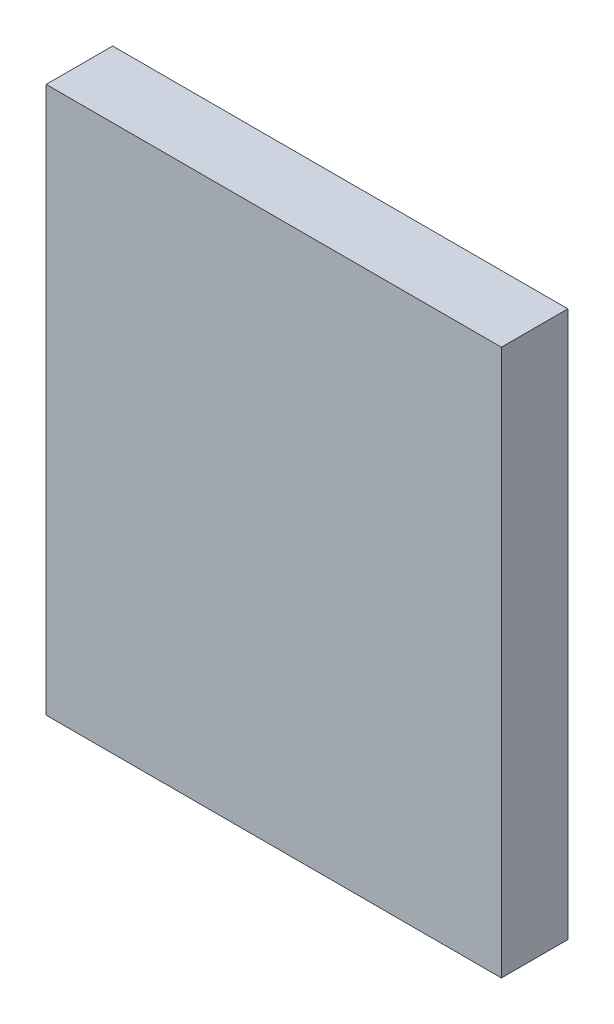
SolidWorks part; units mm, degrees
ref_plane "Front Plane" through (0, 0, 0) normal (0, 0, 1) x (1, 0, 0)
ref_plane "Top Plane" through (0, 0, 0) normal (0, 1, 0) x (1, 0, 0)
ref_plane "Right Plane" through (0, 0, 0) normal (1, 0, 0) x (0, 0, -1)
sketch "Sketch3" plane through (0, 0, 0) normal (0, 0, 1) x (1, 0, 0)
  line L1 (-25, -30) -> (25, -30)
  line L2 (-25, -30) -> (-25, 30)
  line L3 (-25, 30) -> (25, 30)
  line L4 (25, -30) -> (25, 30)
  line L5 (-25, -30) -> (25, 30) construction
  line L6 (-25, 30) -> (25, -30) construction
  point P0 (0, 0)
  dimension "D1" = 50
  dimension "D2" = 60
extrude "Boss-Extrude1" add sketch "Sketch3" along normal blind 7.3
